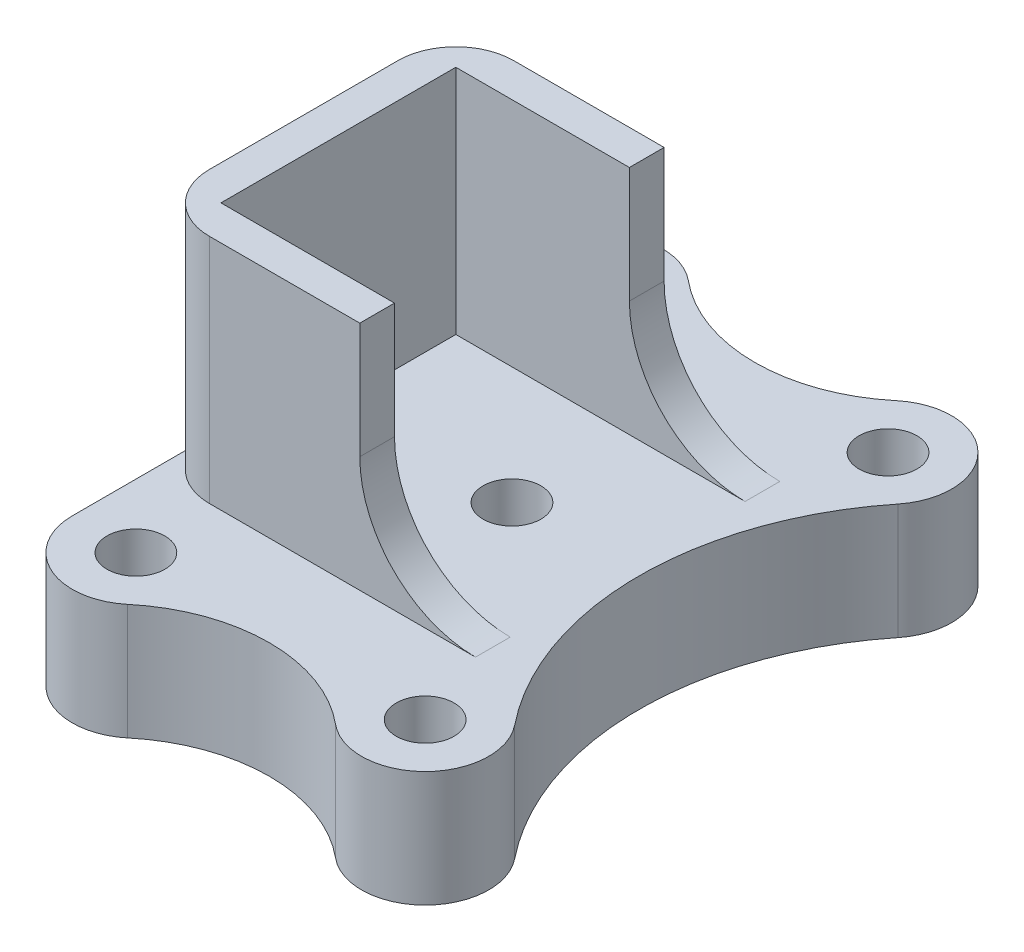
SolidWorks part; units mm, degrees
ref_plane "前视基准面" through (0, 0, 0) normal (0, 0, 1) x (1, 0, 0)
ref_plane "上视基准面" through (0, 0, 0) normal (0, 1, 0) x (1, 0, 0)
ref_plane "右视基准面" through (0, 0, 0) normal (1, 0, 0) x (0, 0, -1)
sketch "Sketch1" plane through (0, 0, 0) normal (0, 1, 0) x (1, 0, 0)
  line L0 (0, 0) -> (0, 20) construction
  line L1 (-12.5, 20) -> (12.5, 20) construction
  line L2 (-12.5, 20) -> (-12.5, -20) construction
  line L3 (-12.5, -20) -> (12.5, -20) construction
  line L4 (12.5, 20) -> (12.5, -20) construction
  line L5 (-12.5, 20) -> (12.5, -20) construction
  line L6 (-12.5, -20) -> (12.5, 20) construction
  line L7 (0, 0) -> (12.5, 0) construction
  line L8 (0, 20) -> (0, 35) construction
  line L9 (12.5, 0) -> (37.5, 0) construction
  line L10 (-18, -20) -> (-18, 20)
  circle A0 centre (-12.5, 20) radius 2.5
  circle A2 centre (12.5, 20) radius 2.5
  circle A3 centre (12.5, -20) radius 2.5
  circle A4 centre (-12.5, -20) radius 2.5
  arc A5 (-8.979, 24.2252) -> (-18, 20) centre (-12.5, 20) ccw
  arc A6 (8.979, 24.2252) -> (16.7948, 16.5642) centre (12.5, 20) cw
  arc A7 (8.979, -24.2252) -> (16.7948, -16.5642) centre (12.5, -20) ccw
  arc A8 (-8.979, -24.2252) -> (-18, -20) centre (-12.5, -20) cw
  arc A9 (-8.979, 24.2252) -> (8.979, 24.2252) centre (0, 35) ccw
  arc A10 (-8.979, -24.2252) -> (8.979, -24.2252) centre (0, -35) cw
  arc A11 (16.7948, 16.5642) -> (16.7948, -16.5642) centre (37.5, 0) ccw
  circle A13 centre (0, 0) radius 2.5
  point P0 (0, 0)
  dimension "D3" = 5
  dimension "D4" = 11
  dimension "D6" = 25
  dimension "D7" = 5
  dimension "D1" = 25
  dimension "D2" = 40
  dimension "D5" = 15
extrude "Boss-Extrude1" add sketch "Sketch1" along normal blind 10
sketch "Sketch3" plane through (0, 0, 0) normal (0, -1, 0) x (1, 0, 0)
  circle A0 centre (0, 0) radius 5.5
  dimension "D1" = 11
extrude "Cut-Extrude1" cut sketch "Sketch3" against normal blind 4
sketch "Sketch4" plane through (0, 10, 0) normal (0, 1, 0) x (1, 0, 0)
  line L0 (0, 0) -> (0, 10.15) construction
  line L1 (0, 10.15) -> (-15, 10.15)
  line L2 (-15, 10.15) -> (-15, 0)
  line L3 (-15, 0) -> (0, 0) construction
  line L4 (-18, 20) -> (-18, -20) construction
  line L5 (0, 13.15) -> (-18, 13.15)
  line L6 (-18, 13.15) -> (-18, 0)
  line L7 (0, 10.15) -> (0, 13.15)
  line L8 (-15, -10.15) -> (-15, 0)
  line L9 (-18, -13.15) -> (-18, 0)
  line L10 (0, -10.15) -> (-15, -10.15)
  line L11 (0, -10.15) -> (0, -13.15)
  line L12 (0, -13.15) -> (-18, -13.15)
  dimension "D1" = 10.15
  dimension "D2" = 3
  dimension "D3" = 3
extrude "Boss-Extrude2" add sketch "Sketch4" along normal blind 20
fillet "Fillet1" radius 10 2 edges at (0, 10, 11.65) (0, 10, -11.65)
fillet "Fillet2" radius 5 2 edges at (-18, 20, 13.15) (-18, 20, -13.15)
